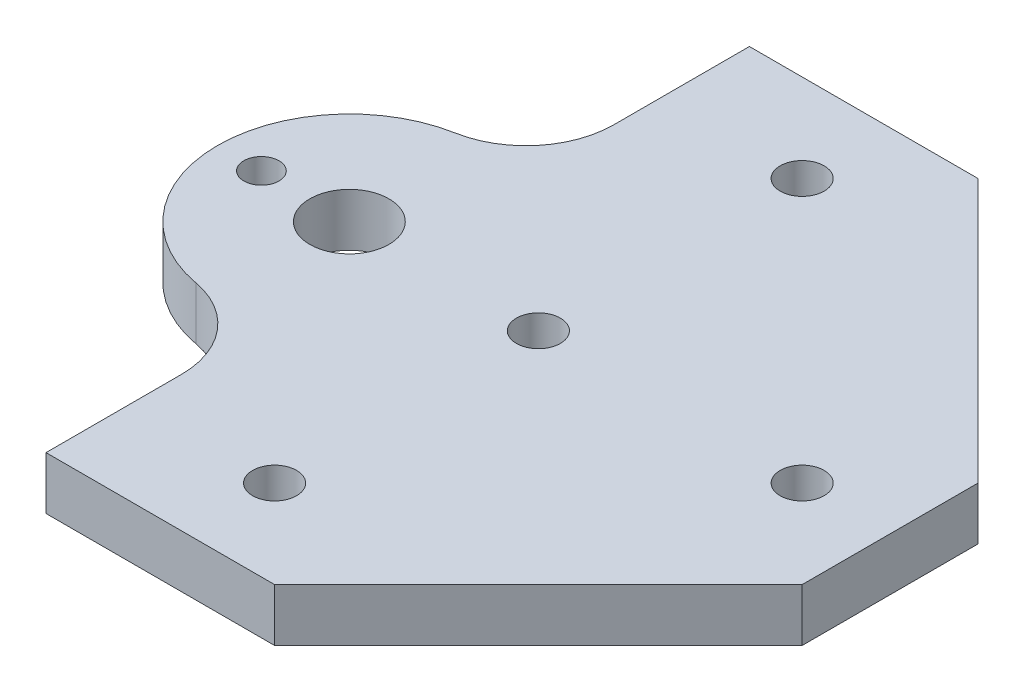
SolidWorks part; units mm, degrees
material "Acrylic (Medium-high impact)"
ref_plane "Front Plane" through (0, 0, 0) normal (0, 0, 1) x (1, 0, 0)
ref_plane "Top Plane" through (0, 0, 0) normal (0, 1, 0) x (1, 0, 0)
ref_plane "Right Plane" through (0, 0, 0) normal (1, 0, 0) x (0, 0, -1)
sketch "Sketch1" plane through (0, 0, 0) normal (0, 1, 0) x (1, 0, 0)
  line L0 (0, 0) -> (0, 10)
  line L1 (0, 10) -> (-30, 40)
  line L2 (-30, 40) -> (-56, 40)
  line L3 (-56, 40) -> (-56, 13.9553)
  line L4 (-56, -40) -> (-30, -40)
  line L5 (-30, -40) -> (0, -10)
  line L6 (0, -10) -> (0, 0)
  line L7 (-56, -13.9553) -> (-56, -40)
  line L9 (-56, 13.9553) -> (-56, -13.9553) construction
  arc A0 (-56, 13.9553) -> (-56, -13.9553) centre (-61.5, 0) ccw
  dimension "D2" = 15
  dimension "D1" = 45
  dimension "D3" = 80
  dimension "D4" = 26
  dimension "D5" = 20
  dimension "D6" = 61.5
extrude "Boss-Extrude1" add sketch "Sketch1" along normal blind 6
fillet "Fillet1" radius 10 2 edges at (-56, 3, -13.9553) (-56, 3, 13.9553)
sketch "Sketch3" plane through (0, 6, 0) normal (0, 1, 0) x (1, 0, 0)
  line L0 (-40, 40) -> (-40, -40) construction
  line L1 (-30, 40) -> (-56, 40) construction
  line L2 (-56, -40) -> (-30, -40) construction
  line L3 (-40, 0) -> (0, 0) construction
  line L4 (0, -10) -> (0, 10) construction
  line L5 (-61.5, 0) -> (-71.5, 0) construction
  circle A0 centre (-40, 0) radius 2.5
  circle A1 centre (-40, -30) radius 2.5
  circle A2 centre (-10, 0) radius 2.5
  circle A3 centre (-40, 30) radius 2.5
  circle A4 centre (-61.5, 0) radius 4.5
  circle A5 centre (-71.5, 0) radius 2
  dimension "D2" = 5
  dimension "D4" = 10
  dimension "D5" = 10
  dimension "D6" = 9
  dimension "D7" = 4
  dimension "D1" = 10
  dimension "D3" = 10
  dimension "D8" = 10
extrude "Cut-Extrude1" cut sketch "Sketch3" against normal through all
